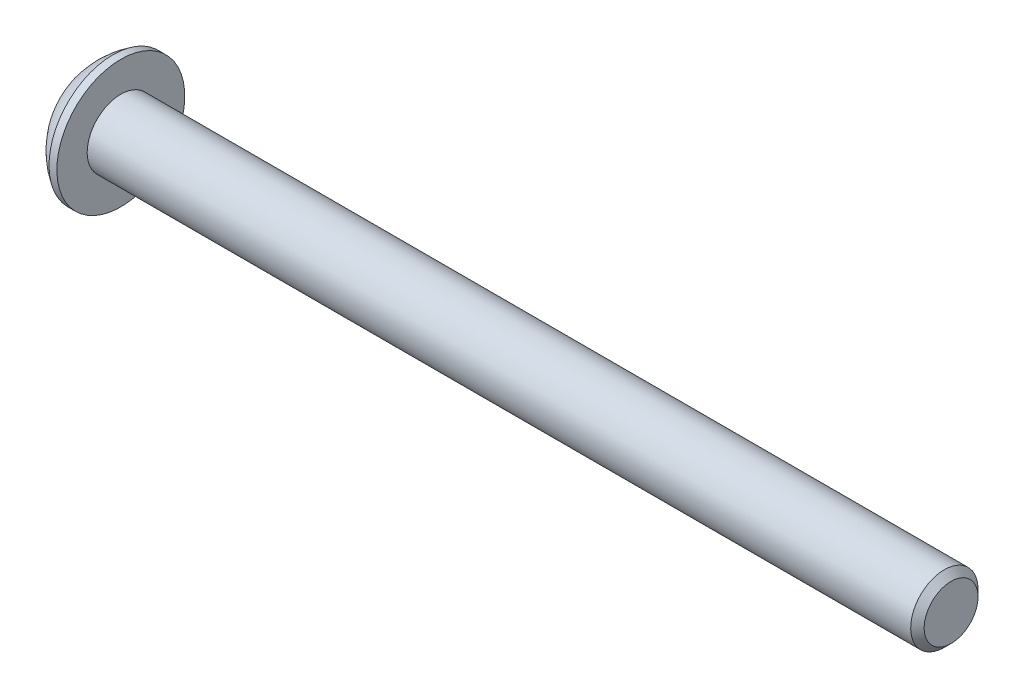
SolidWorks part; units mm, degrees
ref_plane "Front Plane" through (0, 0, 0) normal (0, 0, 1) x (1, 0, 0)
ref_plane "Top Plane" through (0, 0, 0) normal (0, 1, 0) x (1, 0, 0)
ref_plane "Right Plane" through (0, 0, 0) normal (1, 0, 0) x (0, 0, -1)
sketch "Sketch2" plane through (0, 0, 0) normal (0, 0, 1) x (1, 0, 0)
  line L0 (38.65, 0) -> (0, 0)
  line L1 (0, 0) -> (0, 1.43)
  line L2 (1.3, 2.85) -> (1.65, 2.85)
  line L3 (1.65, 2.85) -> (1.65, 1.5)
  line L4 (1.65, 1.5) -> (38.65, 1.5)
  line L5 (38.65, 1.5) -> (38.65, 0)
  arc A0 (1.3, 2.85) -> (0, 1.43) centre (3.132, -0.1322) ccw
  dimension "D1" = 37
  dimension "D6" = 3.5
  dimension "D2" = 1.5
  dimension "D3" = 2.85
  dimension "D4" = 0.35
  dimension "D5" = 1.65
  dimension "D7" = 1.43
revolve "Revolve1" add sketch "Sketch2" angle 360 about L0
chamfer "Chamfer1" distance 0.3 angle 45 1 edges at (38.65, 1.5, 0)
sketch "Sketch3" plane through (0, 0, 0) normal (-1, 0, 0) x (0, 0, 1)
  line L1 (1, -0.5774) -> (1, 0.5774)
  line L2 (1, 0.5774) -> (0, 1.1547)
  line L3 (0, 1.1547) -> (-1, 0.5774)
  line L4 (-1, 0.5774) -> (-1, -0.5774)
  line L5 (-1, -0.5774) -> (0, -1.1547)
  line L6 (0, -1.1547) -> (1, -0.5774)
  circle A0 centre (0, 0) radius 1 construction
  dimension "D1" = 2
extrude "Cut-Extrude1" cut sketch "Sketch3" against normal blind 1
